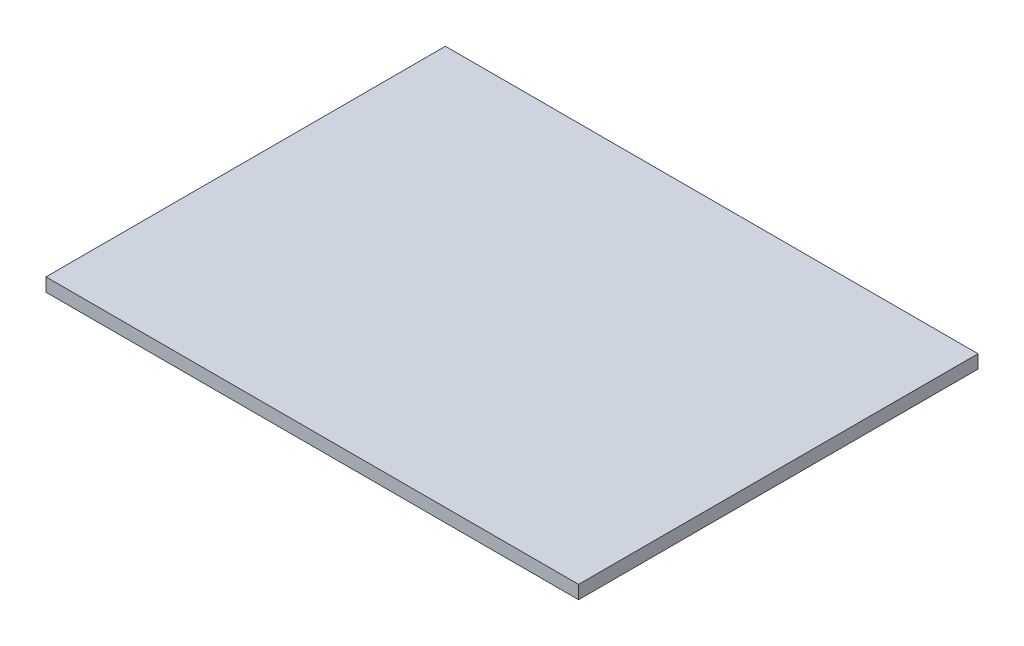
SolidWorks part; units mm, degrees
ref_plane "Alzado" through (0, 0, 0) normal (0, 0, 1) x (1, 0, 0)
ref_plane "Planta" through (0, 0, 0) normal (0, 1, 0) x (1, 0, 0)
ref_plane "Vista lateral" through (0, 0, 0) normal (1, 0, 0) x (0, 0, -1)
sketch "Croquis1" plane through (0, 0, 0) normal (0, 1, 0) x (1, 0, 0)
  line L1 (-20, -15) -> (20, -15)
  line L2 (-20, -15) -> (-20, 15)
  line L3 (-20, 15) -> (20, 15)
  line L4 (20, -15) -> (20, 15)
  line L5 (-20, -15) -> (20, 15) construction
  line L6 (-20, 15) -> (20, -15) construction
  point P0 (0, 0)
  dimension "D1" = 40
  dimension "D2" = 30
extrude "Saliente-Extruir1" add sketch "Croquis1" along normal blind 1
